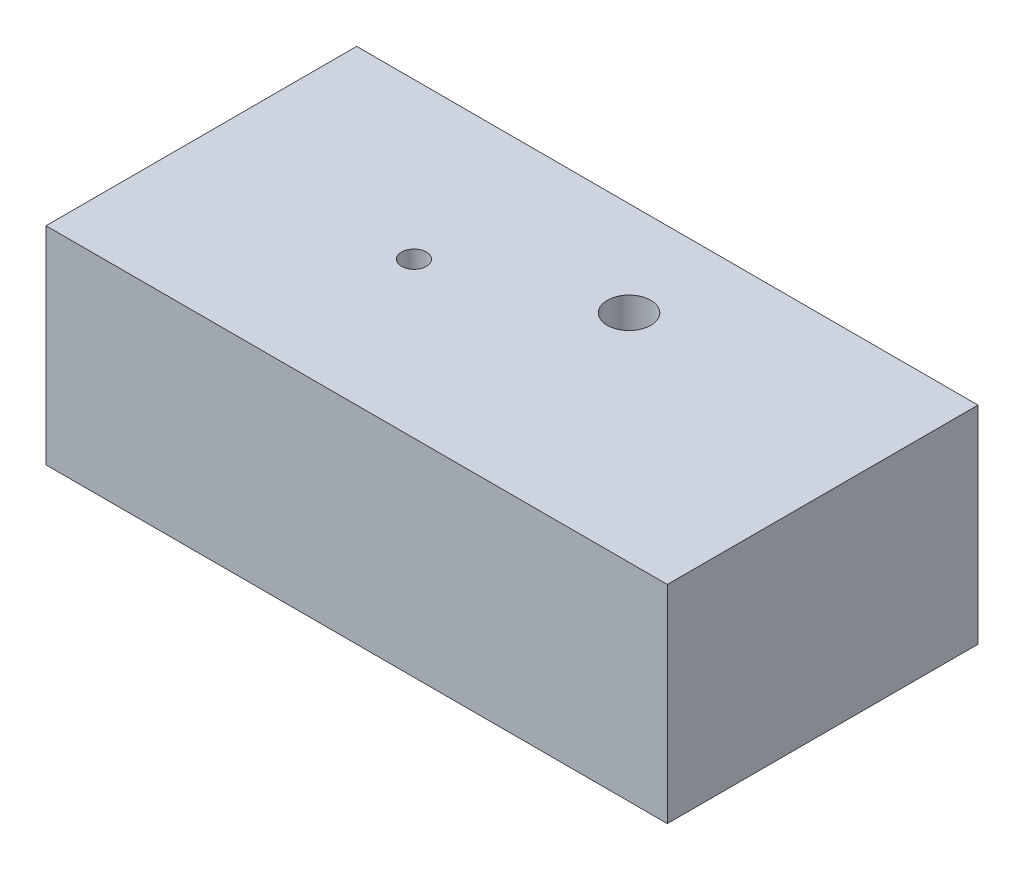
SolidWorks part; units mm, degrees
ref_plane "Front Plane" through (0, 0, 0) normal (0, 0, 1) x (1, 0, 0)
ref_plane "Top Plane" through (0, 0, 0) normal (0, 1, 0) x (1, 0, 0)
ref_plane "Right Plane" through (0, 0, 0) normal (1, 0, 0) x (0, 0, -1)
sketch "Sketch1" plane through (0, 0, 0) normal (0, 1, 0) x (1, 0, 0)
  line L0 (-0.0353, -0.015) -> (-15.0353, -0.015) construction
  line L1 (-15, -7.5) -> (15, -7.5)
  line L2 (-15, -7.5) -> (-15, 7.5)
  line L3 (-15, 7.5) -> (15, 7.5)
  line L4 (15, -7.5) -> (15, 7.5)
  line L5 (0, 0) -> (0, 7.5) construction
  circle A0 centre (2.7176, 2.935) radius 1.05
  circle A1 centre (-4.7186, -0.015) radius 0.6
  dimension "D3" = 2.1
  dimension "D4" = 8
  dimension "D6" = 1.2
  dimension "D1" = 30
  dimension "D2" = 15
  dimension "D5" = 4
extrude "Boss-Extrude1" add sketch "Sketch1" along normal blind 10
